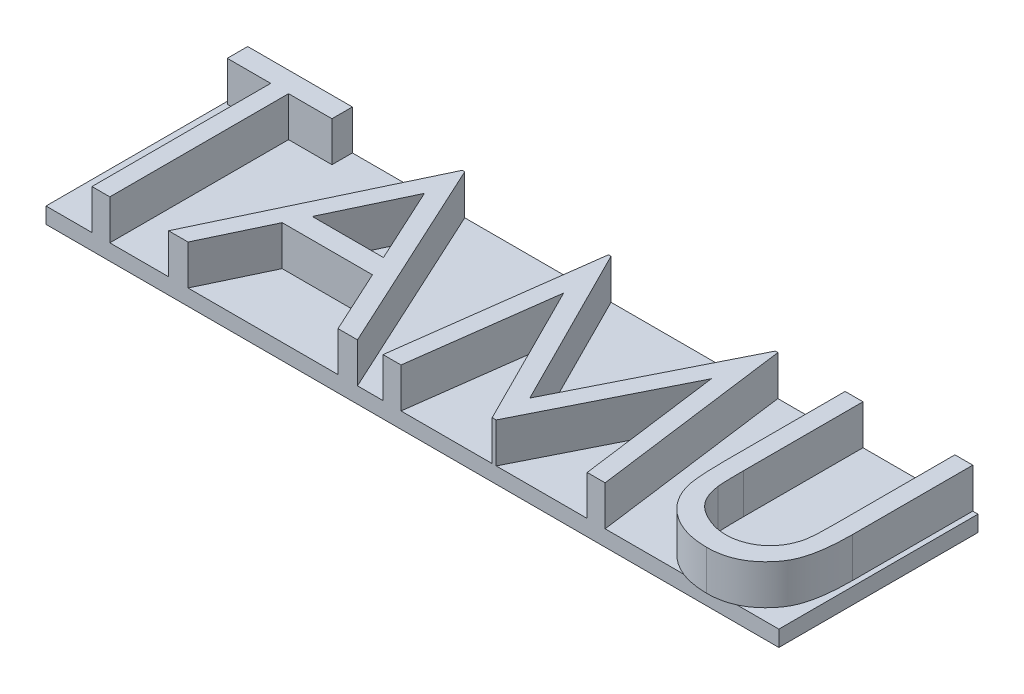
SolidWorks part; units mm, degrees
ref_plane "Front Plane" through (0, 0, 0) normal (0, 0, 1) x (1, 0, 0)
ref_plane "Top Plane" through (0, 0, 0) normal (0, 1, 0) x (1, 0, 0)
ref_plane "Right Plane" through (0, 0, 0) normal (1, 0, 0) x (0, 0, -1)
sketch "Sketch2" plane through (0, 0, 0) normal (0, 1, 0) x (1, 0, 0)
  line L1 (0, 0) -> (116.84, 0)
  line L2 (0, 0) -> (0, -31.75)
  line L3 (0, -31.75) -> (116.84, -31.75)
  line L4 (116.84, 0) -> (116.84, -31.75)
extrude "Boss-Extrude2" add sketch "Sketch2" along normal blind 2.54
sketch "Sketch6" plane through (0, 2.54, 0) normal (0, 1, 0) x (1, 0, 0)
  text T0 "TAMU" font "Century Gothic" height 31.75
extrude "Boss-Extrude5" add sketch "Sketch6" along normal blind 6.35
